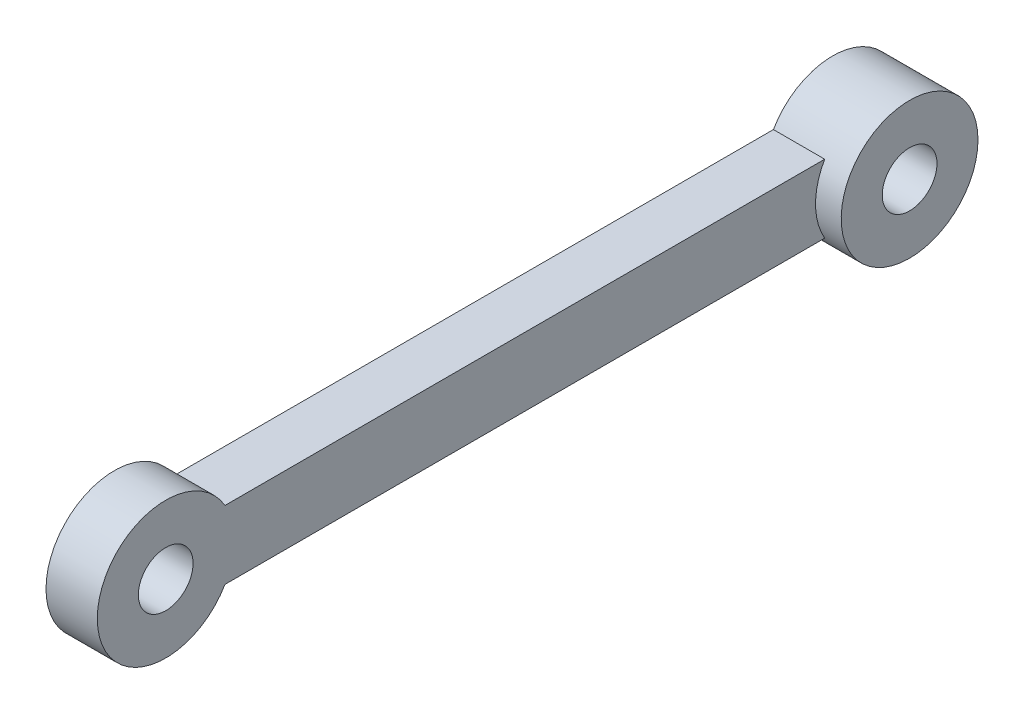
SolidWorks part; units mm, degrees
ref_plane "Front Plane" through (0, 0, 0) normal (0, 0, 1) x (1, 0, 0)
ref_plane "Top Plane" through (0, 0, 0) normal (0, 1, 0) x (1, 0, 0)
ref_plane "Right Plane" through (0, 0, 0) normal (1, 0, 0) x (0, 0, -1)
sketch "Sketch1" plane through (0, 0, 0) normal (1, 0, 0) x (0, 0, -1)
  line L2 (21, 2) -> (38.5359, 2)
  line L3 (21, 2) -> (3.4641, 2)
  line L5 (21, -2) -> (38.5359, -2)
  line L6 (21, -2) -> (3.4641, -2)
  arc A0 (38.5359, -2) -> (38.5359, 2) centre (42, 0) ccw
  arc A1 (3.4641, 2) -> (3.4641, -2) centre (0, 0) ccw
  circle A2 centre (0, 0) radius 1.6
  circle A3 centre (42, 0) radius 1.6
extrude "Boss-Extrude1" add sketch "Sketch1" along normal blind 3
sketch "Sketch3" plane through (3, 0, 0) normal (1, 0, 0) x (0, 0, -1)
  circle A0 centre (42, 0) radius 4
  circle A1 centre (42, 0) radius 1.6
extrude "Boss-Extrude3" add sketch "Sketch3" along normal blind 1.5
